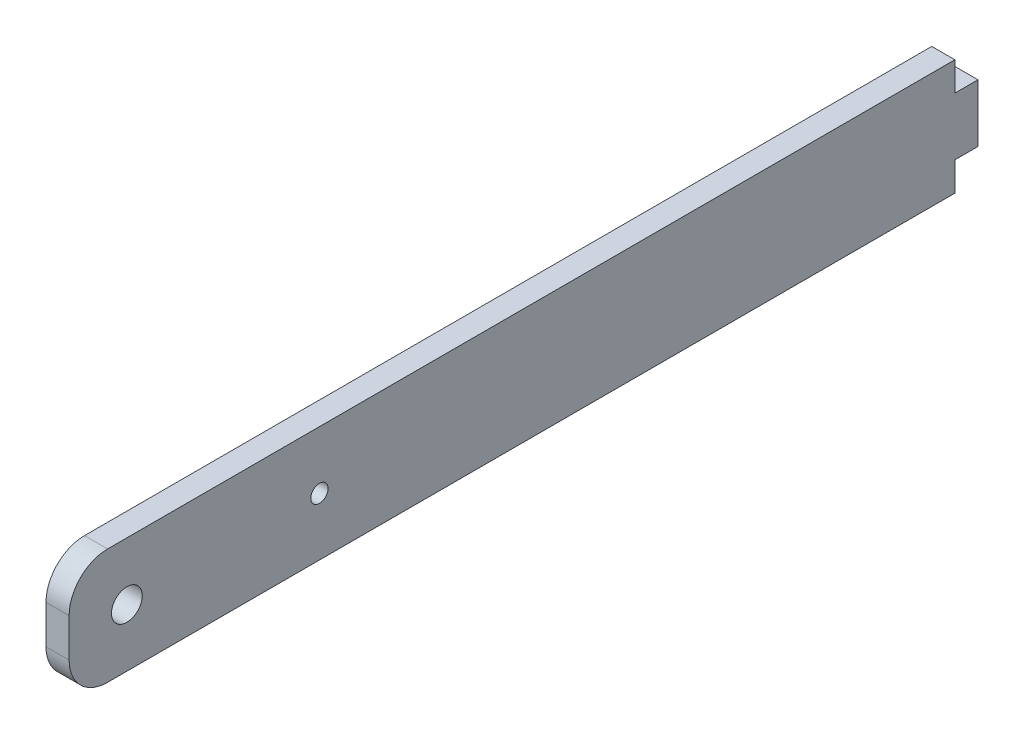
SolidWorks part; units mm, degrees
material "6061-T6 (SS)"
ref_plane "Alzado" through (0, 0, 0) normal (0, 0, 1) x (1, 0, 0)
ref_plane "Planta" through (0, 0, 0) normal (0, 1, 0) x (1, 0, 0)
ref_plane "Vista lateral" through (0, 0, 0) normal (1, 0, 0) x (0, 0, -1)
sketch "Croquis2" plane through (0, 0, 0) normal (1, 0, 0) x (0, 0, -1)
  line L2 (-100, 0) -> (100, 0) construction
  line L3 (-115, 15) -> (115, 15)
  line L4 (-115, 15) -> (-115, -15)
  line L5 (115, 15) -> (115, -15)
  line L6 (115, -15) -> (-115, -15)
  circle A2 centre (-100, 0) radius 4
  circle A3 centre (100, 0) radius 4 construction
  point P3 (-115, 0)
  point P4 (0, 0)
  point P7 (0, 15)
  dimension "D1" = 8
  dimension "D2" = 200
  dimension "D6" = 8
  dimension "D3" = 30
  dimension "D4" = 15
extrude "Saliente-Extruir1" add sketch "Croquis2" along normal mid plane 6
hole_wizard "Taladro de margen para M41" positions "Croquis3" profile "Croquis4" hole size "M4" standard "Ansi Metric" end condition up to next
sketch "Croquis3" plane through (3, 0, 0) normal (1, 0, 0) x (0, 0, -1)
  point P0 (-50, 0)
sketch "Croquis4" plane through (3, 0, 50) normal (0, 1, 0) x (0, 0, -1)
  line L0 (0, 0) -> (0, 6)
  line L1 (0, 6) -> (2.25, 6)
  line L2 (2.25, 6) -> (2.25, 0)
  line L5 (2.25, 0) -> (0, 0)
  line L11 (0, -6.35) -> (0, 107.95) construction
  dimension "Diámetro de taladro hasta el siguiente" = 4.5
  dimension "Profundidad de taladro hasta el siguiente" = 6
fillet "Redondeo1" radius 10 2 edges at (0, -15, 115) (0, 15, 115)
sketch "Croquis5" plane through (3, 0, 0) normal (1, 0, 0) x (0, 0, -1)
  line L0 (115, -15) -> (115, 15) construction
  line L1 (115, 7.5) -> (121, 7.5)
  line L2 (115, 7.5) -> (115, -7.5)
  line L3 (115, -7.5) -> (121, -7.5)
  line L4 (121, 7.5) -> (121, -7.5)
  line L5 (121, 7.5) -> (115, 7.5) construction
  line L6 (121, -7.5) -> (121, 7.5) construction
  line L7 (115, -7.5) -> (121, -7.5) construction
extrude "Saliente-Extruir2" add sketch "Croquis5" against normal through all
